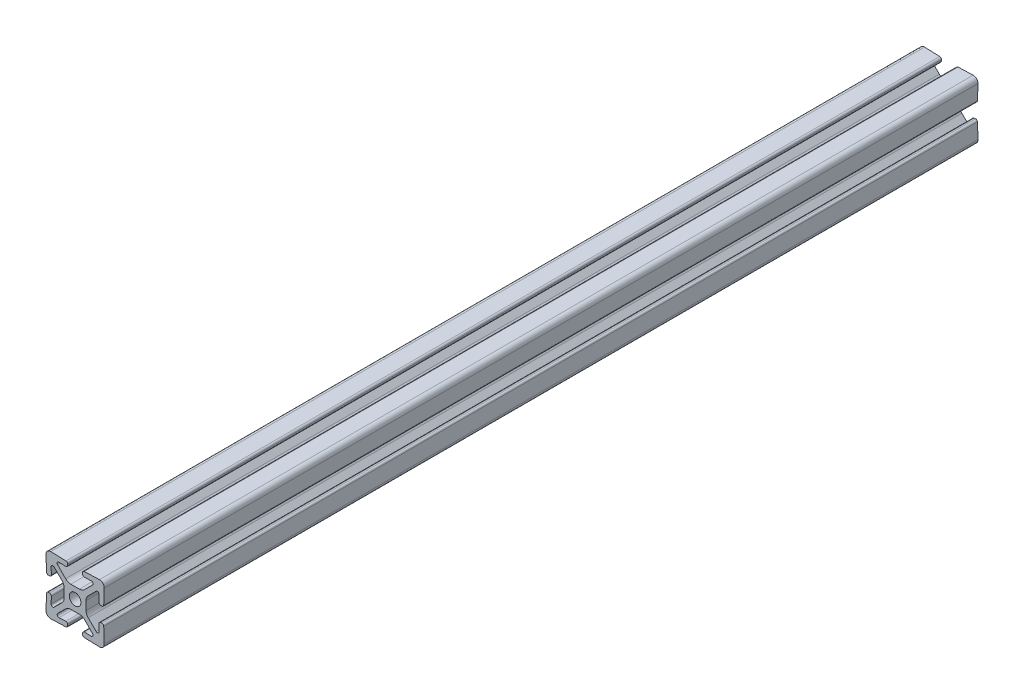
SolidWorks part; units mm, degrees
ref_plane "Front Plane" through (0, 0, 0) normal (0, 0, 1) x (1, 0, 0)
ref_plane "Top Plane" through (0, 0, 0) normal (0, 1, 0) x (1, 0, 0)
ref_plane "Right Plane" through (0, 0, 0) normal (1, 0, 0) x (0, 0, -1)
sketch "Sketch1" plane through (0, 0, 0) normal (0, 0, 1) x (1, 0, 0)
  line L0 (0, 0) -> (0, 12.7) construction
  line L1 (0, 0) -> (12.7, 0) construction
  line L2 (0, 0) -> (-12.7, 12.7) construction
  line L3 (-10.5971, 12.6988) -> (-3.9739, 12.4675)
  line L4 (-12.7, 12.7) -> (0, 12.7) construction
  line L6 (-4.0475, 10.3606) -> (-7.0332, 10.4648)
  line L10 (0, 4.7625) -> (-1.8848, 4.7625)
  line L11 (-4.1299, 5.6924) -> (-7.5996, 9.1622)
  line L24 (0, 0) -> (-12.7, 0) construction
  line L25 (-12.7, 0) -> (0, 0) construction
  line L26 (0, 0) -> (0, -12.7) construction
  line L27 (-12.7, -12.7) -> (-12.7, 12.7) construction
  line L28 (0, 12.7) -> (12.7, 12.7) construction
  line L29 (-3.239, 11.6793) -> (-3.2594, 11.0955)
  line L30 (-12.7, -12.7) -> (12.7, -12.7) construction
  arc A0 (-12.1048, 12.1048) -> (-10.5971, 12.6988) centre (-10.668, 10.668) cw
  arc A6 (-1.8848, 4.7625) -> (-4.1299, 5.6924) centre (-1.8848, 7.9375) cw
  circle A16 centre (0, 0) radius 2.54
  arc A18 (-7.5996, 9.1622) -> (-7.0332, 10.4648) centre (-7.0599, 9.702) cw
  circle A19 centre (-2.3794, 2.3794) radius 0.635 construction
  arc A20 (-4.0475, 10.3606) -> (-3.2594, 11.0955) centre (-4.0209, 11.1221) ccw
  arc A21 (-3.9739, 12.4675) -> (-3.239, 11.6793) centre (-4.0005, 11.7059) cw
  point P15 (0, 0)
  point P42 (-3.1999, 4.7625)
  point P80 (-12.7, 0)
  point P85 (0, -12.7)
  point P88 (0, -12.7)
  dimension "D11" = 2.032
  dimension "D15" = 3.175
  dimension "Center Hole Diameter" = 5.08
  dimension "D6" = 1.27
  dimension "D4" = 0.7633
  dimension "D8" = 0.762
  dimension "D12" = 0.762
  dimension "D1" = 45
  dimension "D2" = 2
  dimension "Rail Width" = 25.4
  dimension "D10" = 2.2098
  dimension "T-Slot Depth" = 7.9375
  dimension "D9" = 2.1082
  dimension "Rail Height" = 25.4
  dimension "D23" = 9.525
  dimension "D5" = 15.6464
  dimension "D3" = 4
  dimension "D7" = 5.7028
  dimension "T-Slot Width" = 6.477
sketch "Sketch2" plane through (0, 0, 0) normal (1, 0, 0) x (0, 0, -1)
  line L0 (-609.6, 0) -> (609.6, 0)
  line L2 (0, 0) -> (0, 12.7) construction
  line L3 (0, 0) -> (0, 12.7) construction
  point P0 (-571.5, 0)
  point P3 (0, 0)
  point P7 (571.5, 0)
  dimension "D1" = 38.1
  dimension "Length" = 1219.2
sketch "Sketch3" plane through (0, 0, 0) normal (0, 0, 1) x (1, 0, 0)
  line L2 (0, 4.7625) -> (-1.8848, 4.7625) construction
  line L5 (-4.1299, 5.6924) -> (-7.5996, 9.1622) construction
  line L6 (-4.0475, 10.3606) -> (-7.0332, 10.4648) construction
  line L7 (-3.239, 11.6793) -> (-3.2594, 11.0955) construction
  line L67 (-10.5971, 12.6988) -> (-3.9739, 12.4675) construction
  line L68 (0, 4.7625) -> (-1.8848, 4.7625)
  line L69 (-4.1299, 5.6924) -> (-7.5996, 9.1622)
  line L70 (-4.0475, 10.3606) -> (-7.0332, 10.4648)
  line L71 (-3.239, 11.6793) -> (-3.2594, 11.0955)
  line L72 (-10.5971, 12.6988) -> (-3.9739, 12.4675)
  line L73 (0, 0) -> (-12.7, 12.7) construction
  line L74 (0, 0) -> (-12.7, 12.7) construction
  line L75 (-12.6988, 10.5971) -> (-12.4675, 3.9739)
  line L76 (-11.6793, 3.239) -> (-11.0955, 3.2594)
  line L77 (-10.3606, 4.0475) -> (-10.4648, 7.0332)
  line L78 (-5.6924, 4.1299) -> (-9.1622, 7.5996)
  line L79 (-4.7625, 0) -> (-4.7625, 1.8848)
  line L80 (-4.7625, 0) -> (-2.54, 0)
  line L82 (0, 4.7625) -> (0, 2.54)
  arc A3 (-4.1299, 5.6924) -> (-1.8848, 4.7625) centre (-1.8848, 7.9375) ccw construction
  circle A10 centre (0, 0) radius 2.54
  arc A56 (0, 2.54) -> (-2.54, 0) centre (0, 0) ccw
  arc A57 (-7.0332, 10.4648) -> (-7.5996, 9.1622) centre (-7.0599, 9.702) ccw construction
  arc A58 (-4.0475, 10.3606) -> (-3.2594, 11.0955) centre (-4.0209, 11.1221) ccw construction
  arc A59 (-3.239, 11.6793) -> (-3.9739, 12.4675) centre (-4.0005, 11.7059) ccw construction
  arc A60 (-10.5971, 12.6988) -> (-12.1048, 12.1048) centre (-10.668, 10.668) ccw construction
  arc A61 (-4.1299, 5.6924) -> (-1.8848, 4.7625) centre (-1.8848, 7.9375) ccw
  arc A62 (-7.0332, 10.4648) -> (-7.5996, 9.1622) centre (-7.0599, 9.702) ccw
  arc A63 (-4.0475, 10.3606) -> (-3.2594, 11.0955) centre (-4.0209, 11.1221) ccw
  arc A64 (-3.239, 11.6793) -> (-3.9739, 12.4675) centre (-4.0005, 11.7059) ccw
  arc A65 (-10.5971, 12.6988) -> (-12.6988, 10.5971) centre (-10.668, 10.668) ccw
  arc A67 (-11.6793, 3.239) -> (-12.4675, 3.9739) centre (-11.7059, 4.0005) cw
  arc A68 (-10.3606, 4.0475) -> (-11.0955, 3.2594) centre (-11.1221, 4.0209) cw
  arc A69 (-10.4648, 7.0332) -> (-9.1622, 7.5996) centre (-9.702, 7.0599) cw
  arc A70 (-5.6924, 4.1299) -> (-4.7625, 1.8848) centre (-7.9375, 1.8848) cw
  dimension "D1" = 0
extrude "Boss-Extrude1" add sketch "Sketch3" along normal mid plane 1219.2
pattern_circular "CirPattern1" count 4 over 360 about axis through (0, 0, 0) along (0, 0, 1) of "Boss-Extrude1"
ref_plane "Contact Plane 1" through (0, 12.7, 0) normal (0, 1, 0) x (1, 0, 0)
ref_plane "Contact Plane 2" through (12.7, 0, 0) normal (1, 0, 0) x (0, 0, -1)
ref_plane "Contact Plane 3" through (0, -12.7, 0) normal (0, -1, 0) x (-1, 0, 0)
ref_plane "Contact Plane 4" through (-12.7, 0, 0) normal (-1, 0, 0) x (0, 0, 1)
sketch "Sketch4" plane through (0, 0, 609.6) normal (0, 0, 1) x (1, 0, 0)
  line L36 (1.8848, 4.7625) -> (-1.8848, 4.7625)
  line L37 (-4.1299, 5.6924) -> (-7.5996, 9.1622)
  line L38 (-7.0332, 10.4648) -> (-4.0475, 10.3606)
  line L39 (-3.2594, 11.0955) -> (-3.239, 11.6793)
  line L40 (-3.9739, 12.4675) -> (-10.5971, 12.6988)
  line L41 (-12.6988, 10.5971) -> (-12.4675, 3.9739)
  line L42 (-11.6793, 3.239) -> (-11.0955, 3.2594)
  line L43 (-10.3606, 4.0475) -> (-10.4648, 7.0332)
  line L44 (-9.1622, 7.5996) -> (-5.6924, 4.1299)
  line L45 (-4.7625, 1.8848) -> (-4.7625, -1.8848)
  line L46 (-5.6924, -4.1299) -> (-9.1622, -7.5996)
  line L47 (-10.4648, -7.0332) -> (-10.3606, -4.0475)
  line L48 (-11.0955, -3.2594) -> (-11.6793, -3.239)
  line L49 (-12.4675, -3.9739) -> (-12.6988, -10.5971)
  line L50 (-10.5971, -12.6988) -> (-3.9739, -12.4675)
  line L51 (-3.239, -11.6793) -> (-3.2594, -11.0955)
  line L52 (-4.0475, -10.3606) -> (-7.0332, -10.4648)
  line L53 (-7.5996, -9.1622) -> (-4.1299, -5.6924)
  line L54 (-1.8848, -4.7625) -> (1.8848, -4.7625)
  line L55 (4.1299, -5.6924) -> (7.5996, -9.1622)
  line L56 (7.0332, -10.4648) -> (4.0475, -10.3606)
  line L57 (3.2594, -11.0955) -> (3.239, -11.6793)
  line L58 (3.9739, -12.4675) -> (10.5971, -12.6988)
  line L59 (12.6988, -10.5971) -> (12.4675, -3.9739)
  line L60 (11.6793, -3.239) -> (11.0955, -3.2594)
  line L61 (10.3606, -4.0475) -> (10.4648, -7.0332)
  line L62 (9.1622, -7.5996) -> (5.6924, -4.1299)
  line L63 (4.7625, -1.8848) -> (4.7625, 1.8848)
  line L64 (5.6924, 4.1299) -> (9.1622, 7.5996)
  line L65 (10.4648, 7.0332) -> (10.3606, 4.0475)
  line L66 (11.0955, 3.2594) -> (11.6793, 3.239)
  line L67 (12.4675, 3.9739) -> (12.6988, 10.5971)
  line L68 (10.5971, 12.6988) -> (3.9739, 12.4675)
  line L69 (3.239, 11.6793) -> (3.2594, 11.0955)
  line L70 (4.0475, 10.3606) -> (7.0332, 10.4648)
  line L71 (7.5996, 9.1622) -> (4.1299, 5.6924)
  line L72 (1.8848, 4.7625) -> (-1.8848, 4.7625)
  line L73 (-4.1299, 5.6924) -> (-7.5996, 9.1622)
  line L74 (-7.0332, 10.4648) -> (-4.0475, 10.3606)
  line L75 (-3.2594, 11.0955) -> (-3.239, 11.6793)
  line L76 (-3.9739, 12.4675) -> (-10.5971, 12.6988)
  line L77 (-12.6988, 10.5971) -> (-12.4675, 3.9739)
  line L78 (-11.6793, 3.239) -> (-11.0955, 3.2594)
  line L79 (-10.3606, 4.0475) -> (-10.4648, 7.0332)
  line L80 (-9.1622, 7.5996) -> (-5.6924, 4.1299)
  line L81 (-4.7625, 1.8848) -> (-4.7625, -1.8848)
  line L82 (-5.6924, -4.1299) -> (-9.1622, -7.5996)
  line L83 (-10.4648, -7.0332) -> (-10.3606, -4.0475)
  line L84 (-11.0955, -3.2594) -> (-11.6793, -3.239)
  line L85 (-12.4675, -3.9739) -> (-12.6988, -10.5971)
  line L86 (-10.5971, -12.6988) -> (-3.9739, -12.4675)
  line L87 (-3.239, -11.6793) -> (-3.2594, -11.0955)
  line L88 (-4.0475, -10.3606) -> (-7.0332, -10.4648)
  line L89 (-7.5996, -9.1622) -> (-4.1299, -5.6924)
  line L90 (-1.8848, -4.7625) -> (1.8848, -4.7625)
  line L91 (4.1299, -5.6924) -> (7.5996, -9.1622)
  line L92 (7.0332, -10.4648) -> (4.0475, -10.3606)
  line L93 (3.2594, -11.0955) -> (3.239, -11.6793)
  line L94 (3.9739, -12.4675) -> (10.5971, -12.6988)
  line L95 (12.6988, -10.5971) -> (12.4675, -3.9739)
  line L96 (11.6793, -3.239) -> (11.0955, -3.2594)
  line L97 (10.3606, -4.0475) -> (10.4648, -7.0332)
  line L98 (9.1622, -7.5996) -> (5.6924, -4.1299)
  line L99 (4.7625, -1.8848) -> (4.7625, 1.8848)
  line L100 (5.6924, 4.1299) -> (9.1622, 7.5996)
  line L101 (10.4648, 7.0332) -> (10.3606, 4.0475)
  line L102 (11.0955, 3.2594) -> (11.6793, 3.239)
  line L103 (12.4675, 3.9739) -> (12.6988, 10.5971)
  line L104 (10.5971, 12.6988) -> (3.9739, 12.4675)
  line L105 (3.239, 11.6793) -> (3.2594, 11.0955)
  line L106 (4.0475, 10.3606) -> (7.0332, 10.4648)
  line L107 (7.5996, 9.1622) -> (4.1299, 5.6924)
  arc A36 (1.8848, 4.7625) -> (4.1299, 5.6924) centre (1.8848, 7.9375) ccw
  arc A37 (-4.1299, 5.6924) -> (-1.8848, 4.7625) centre (-1.8848, 7.9375) ccw
  arc A38 (-7.0332, 10.4648) -> (-7.5996, 9.1622) centre (-7.0599, 9.702) ccw
  arc A39 (-4.0475, 10.3606) -> (-3.2594, 11.0955) centre (-4.0209, 11.1221) ccw
  arc A40 (-3.239, 11.6793) -> (-3.9739, 12.4675) centre (-4.0005, 11.7059) ccw
  arc A41 (-10.5971, 12.6988) -> (-12.6988, 10.5971) centre (-10.668, 10.668) ccw
  arc A42 (-12.4675, 3.9739) -> (-11.6793, 3.239) centre (-11.7059, 4.0005) ccw
  arc A43 (-11.0955, 3.2594) -> (-10.3606, 4.0475) centre (-11.1221, 4.0209) ccw
  arc A44 (-9.1622, 7.5996) -> (-10.4648, 7.0332) centre (-9.702, 7.0599) ccw
  arc A45 (-4.7625, 1.8848) -> (-5.6924, 4.1299) centre (-7.9375, 1.8848) ccw
  arc A46 (-5.6924, -4.1299) -> (-4.7625, -1.8848) centre (-7.9375, -1.8848) ccw
  arc A47 (-10.4648, -7.0332) -> (-9.1622, -7.5996) centre (-9.702, -7.0599) ccw
  arc A48 (-10.3606, -4.0475) -> (-11.0955, -3.2594) centre (-11.1221, -4.0209) ccw
  arc A49 (-11.6793, -3.239) -> (-12.4675, -3.9739) centre (-11.7059, -4.0005) ccw
  arc A50 (-12.6988, -10.5971) -> (-10.5971, -12.6988) centre (-10.668, -10.668) ccw
  arc A51 (-3.9739, -12.4675) -> (-3.239, -11.6793) centre (-4.0005, -11.7059) ccw
  arc A52 (-3.2594, -11.0955) -> (-4.0475, -10.3606) centre (-4.0209, -11.1221) ccw
  arc A53 (-7.5996, -9.1622) -> (-7.0332, -10.4648) centre (-7.0599, -9.702) ccw
  arc A54 (-1.8848, -4.7625) -> (-4.1299, -5.6924) centre (-1.8848, -7.9375) ccw
  arc A55 (4.1299, -5.6924) -> (1.8848, -4.7625) centre (1.8848, -7.9375) ccw
  arc A56 (7.0332, -10.4648) -> (7.5996, -9.1622) centre (7.0599, -9.702) ccw
  arc A57 (4.0475, -10.3606) -> (3.2594, -11.0955) centre (4.0209, -11.1221) ccw
  arc A58 (3.239, -11.6793) -> (3.9739, -12.4675) centre (4.0005, -11.7059) ccw
  arc A59 (10.5971, -12.6988) -> (12.6988, -10.5971) centre (10.668, -10.668) ccw
  arc A60 (12.4675, -3.9739) -> (11.6793, -3.239) centre (11.7059, -4.0005) ccw
  arc A61 (11.0955, -3.2594) -> (10.3606, -4.0475) centre (11.1221, -4.0209) ccw
  arc A62 (9.1622, -7.5996) -> (10.4648, -7.0332) centre (9.702, -7.0599) ccw
  arc A63 (4.7625, -1.8848) -> (5.6924, -4.1299) centre (7.9375, -1.8848) ccw
  arc A64 (5.6924, 4.1299) -> (4.7625, 1.8848) centre (7.9375, 1.8848) ccw
  arc A65 (10.4648, 7.0332) -> (9.1622, 7.5996) centre (9.702, 7.0599) ccw
  arc A66 (10.3606, 4.0475) -> (11.0955, 3.2594) centre (11.1221, 4.0209) ccw
  arc A67 (11.6793, 3.239) -> (12.4675, 3.9739) centre (11.7059, 4.0005) ccw
  arc A68 (12.6988, 10.5971) -> (10.5971, 12.6988) centre (10.668, 10.668) ccw
  arc A69 (3.9739, 12.4675) -> (3.239, 11.6793) centre (4.0005, 11.7059) ccw
  arc A70 (3.2594, 11.0955) -> (4.0475, 10.3606) centre (4.0209, 11.1221) ccw
  arc A71 (7.5996, 9.1622) -> (7.0332, 10.4648) centre (7.0599, 9.702) ccw
  arc A72 (1.8848, 4.7625) -> (4.1299, 5.6924) centre (1.8848, 7.9375) ccw
  arc A73 (-4.1299, 5.6924) -> (-1.8848, 4.7625) centre (-1.8848, 7.9375) ccw
  arc A74 (-7.0332, 10.4648) -> (-7.5996, 9.1622) centre (-7.0599, 9.702) ccw
  arc A75 (-4.0475, 10.3606) -> (-3.2594, 11.0955) centre (-4.0209, 11.1221) ccw
  arc A76 (-3.239, 11.6793) -> (-3.9739, 12.4675) centre (-4.0005, 11.7059) ccw
  arc A77 (-10.5971, 12.6988) -> (-12.6988, 10.5971) centre (-10.668, 10.668) ccw
  arc A78 (-12.4675, 3.9739) -> (-11.6793, 3.239) centre (-11.7059, 4.0005) ccw
  arc A79 (-11.0955, 3.2594) -> (-10.3606, 4.0475) centre (-11.1221, 4.0209) ccw
  arc A80 (-9.1622, 7.5996) -> (-10.4648, 7.0332) centre (-9.702, 7.0599) ccw
  arc A81 (-4.7625, 1.8848) -> (-5.6924, 4.1299) centre (-7.9375, 1.8848) ccw
  arc A82 (-5.6924, -4.1299) -> (-4.7625, -1.8848) centre (-7.9375, -1.8848) ccw
  arc A83 (-10.4648, -7.0332) -> (-9.1622, -7.5996) centre (-9.702, -7.0599) ccw
  arc A84 (-10.3606, -4.0475) -> (-11.0955, -3.2594) centre (-11.1221, -4.0209) ccw
  arc A85 (-11.6793, -3.239) -> (-12.4675, -3.9739) centre (-11.7059, -4.0005) ccw
  arc A86 (-12.6988, -10.5971) -> (-10.5971, -12.6988) centre (-10.668, -10.668) ccw
  arc A87 (-3.9739, -12.4675) -> (-3.239, -11.6793) centre (-4.0005, -11.7059) ccw
  arc A88 (-3.2594, -11.0955) -> (-4.0475, -10.3606) centre (-4.0209, -11.1221) ccw
  arc A89 (-7.5996, -9.1622) -> (-7.0332, -10.4648) centre (-7.0599, -9.702) ccw
  arc A90 (-1.8848, -4.7625) -> (-4.1299, -5.6924) centre (-1.8848, -7.9375) ccw
  arc A91 (4.1299, -5.6924) -> (1.8848, -4.7625) centre (1.8848, -7.9375) ccw
  arc A92 (7.0332, -10.4648) -> (7.5996, -9.1622) centre (7.0599, -9.702) ccw
  arc A93 (4.0475, -10.3606) -> (3.2594, -11.0955) centre (4.0209, -11.1221) ccw
  arc A94 (3.239, -11.6793) -> (3.9739, -12.4675) centre (4.0005, -11.7059) ccw
  arc A95 (10.5971, -12.6988) -> (12.6988, -10.5971) centre (10.668, -10.668) ccw
  arc A96 (12.4675, -3.9739) -> (11.6793, -3.239) centre (11.7059, -4.0005) ccw
  arc A97 (11.0955, -3.2594) -> (10.3606, -4.0475) centre (11.1221, -4.0209) ccw
  arc A98 (9.1622, -7.5996) -> (10.4648, -7.0332) centre (9.702, -7.0599) ccw
  arc A99 (4.7625, -1.8848) -> (5.6924, -4.1299) centre (7.9375, -1.8848) ccw
  arc A100 (5.6924, 4.1299) -> (4.7625, 1.8848) centre (7.9375, 1.8848) ccw
  arc A101 (10.4648, 7.0332) -> (9.1622, 7.5996) centre (9.702, 7.0599) ccw
  arc A102 (10.3606, 4.0475) -> (11.0955, 3.2594) centre (11.1221, 4.0209) ccw
  arc A103 (11.6793, 3.239) -> (12.4675, 3.9739) centre (11.7059, 4.0005) ccw
  arc A104 (12.6988, 10.5971) -> (10.5971, 12.6988) centre (10.668, 10.668) ccw
  arc A105 (3.9739, 12.4675) -> (3.239, 11.6793) centre (4.0005, 11.7059) ccw
  arc A106 (3.2594, 11.0955) -> (4.0475, 10.3606) centre (4.0209, 11.1221) ccw
  arc A107 (7.5996, 9.1622) -> (7.0332, 10.4648) centre (7.0599, 9.702) ccw
  dimension "D1" = 0
extrude "Cut-Extrude1" cut sketch "Sketch4" against normal offset from surface (838.2 mm away) 381
equation "\"D1@Sketch2\"=\"Rail Width@Sketch1\"*1.5"
equation "\"D1@Boss-Extrude1\"=\"Length@Sketch2\""
